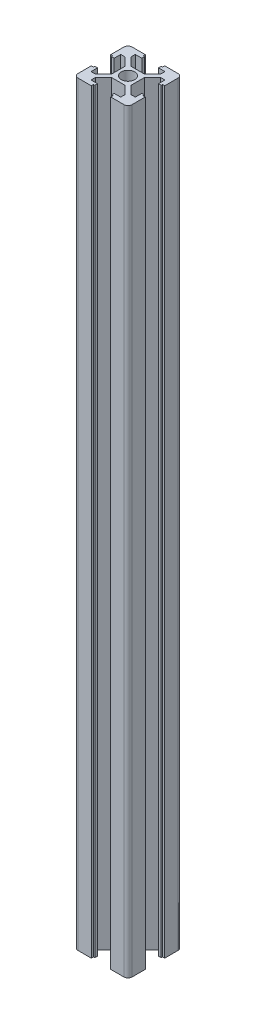
SolidWorks part; units mm, degrees
ref_plane "前视基准面" through (0, 0, 0) normal (0, 0, 1) x (1, 0, 0)
ref_plane "上视基准面" through (0, 0, 0) normal (0, 1, 0) x (1, 0, 0)
ref_plane "右视基准面" through (0, 0, 0) normal (1, 0, 0) x (0, 0, -1)
other "Configuration Table"
sketch "草图1" plane through (0, 0, 0) normal (0, 1, 0) x (1, 0, 0)
  line L0 (15.7522, 51.0126) -> (15.7522, 54.1126) construction
  line L1 (15.7522, 53.552) -> (15.7522, 48.4733)
  line L2 (21.8915, 54.6126) -> (16.8128, 54.6126)
  line L3 (22.9522, 48.4733) -> (22.9522, 53.552)
  line L4 (16.8128, 47.4126) -> (21.8915, 47.4126)
  line L5 (9.3522, 51.0126) -> (29.3522, 51.0126) construction
  line L6 (19.3522, 61.0126) -> (19.3522, 41.0126) construction
  line L7 (9.3522, 61.0126) -> (19.3522, 51.0126) construction
  line L8 (9.3522, 54.6126) -> (15.7522, 54.6126) construction
  line L9 (10.1522, 54.1126) -> (16.2522, 54.1126) construction
  line L10 (11.1522, 56.5126) -> (13.8522, 56.5126) construction
  line L11 (12.7915, 56.5126) -> (15.7522, 53.552) construction
  line L12 (9.3522, 59.5126) -> (9.3522, 54.6126)
  line L13 (9.3522, 54.6126) -> (10.1522, 54.6126)
  line L14 (10.1522, 54.6126) -> (10.1522, 54.1126)
  line L15 (10.1522, 54.1126) -> (11.1522, 54.1126)
  line L16 (11.1522, 54.1126) -> (11.1522, 56.5126)
  line L17 (11.1522, 56.5126) -> (12.7915, 56.5126)
  line L18 (12.7915, 56.5126) -> (15.7522, 53.552)
  line L19 (16.2522, 60.2126) -> (16.2522, 59.2126)
  line L20 (15.7522, 60.2126) -> (16.2522, 60.2126)
  line L21 (15.7522, 61.0126) -> (15.7522, 60.2126)
  line L22 (10.8522, 61.0126) -> (15.7522, 61.0126)
  line L23 (16.2522, 59.2126) -> (13.8522, 59.2126)
  line L24 (13.8522, 59.2126) -> (13.8522, 57.5733)
  line L25 (13.8522, 57.5733) -> (16.8128, 54.6126)
  line L26 (29.3522, 61.0126) -> (19.3522, 51.0126) construction
  line L27 (24.8522, 57.5733) -> (21.8915, 54.6126)
  line L28 (24.8522, 59.2126) -> (24.8522, 57.5733)
  line L29 (22.4522, 59.2126) -> (24.8522, 59.2126)
  line L30 (22.4522, 60.2126) -> (22.4522, 59.2126)
  line L31 (22.9522, 60.2126) -> (22.4522, 60.2126)
  line L32 (22.9522, 61.0126) -> (22.9522, 60.2126)
  line L33 (27.8522, 61.0126) -> (22.9522, 61.0126)
  line L34 (29.3522, 59.5126) -> (29.3522, 54.6126)
  line L35 (29.3522, 54.6126) -> (28.5522, 54.6126)
  line L36 (28.5522, 54.6126) -> (28.5522, 54.1126)
  line L37 (28.5522, 54.1126) -> (27.5522, 54.1126)
  line L38 (27.5522, 54.1126) -> (27.5522, 56.5126)
  line L39 (27.5522, 56.5126) -> (25.9128, 56.5126)
  line L40 (25.9128, 56.5126) -> (22.9522, 53.552)
  line L41 (29.3522, 41.0126) -> (19.3522, 51.0126) construction
  line L42 (25.9128, 45.5126) -> (22.9522, 48.4733)
  line L43 (27.5522, 45.5126) -> (25.9128, 45.5126)
  line L44 (27.5522, 47.9126) -> (27.5522, 45.5126)
  line L45 (28.5522, 47.9126) -> (27.5522, 47.9126)
  line L46 (28.5522, 47.4126) -> (28.5522, 47.9126)
  line L47 (29.3522, 47.4126) -> (28.5522, 47.4126)
  line L48 (29.3522, 42.5126) -> (29.3522, 47.4126)
  line L49 (27.8522, 41.0126) -> (22.9522, 41.0126)
  line L50 (22.9522, 41.0126) -> (22.9522, 41.8126)
  line L51 (22.9522, 41.8126) -> (22.4522, 41.8126)
  line L52 (22.4522, 41.8126) -> (22.4522, 42.8126)
  line L53 (22.4522, 42.8126) -> (24.8522, 42.8126)
  line L54 (24.8522, 42.8126) -> (24.8522, 44.452)
  line L55 (24.8522, 44.452) -> (21.8915, 47.4126)
  line L56 (9.3522, 41.0126) -> (19.3522, 51.0126) construction
  line L57 (13.8522, 44.452) -> (16.8128, 47.4126)
  line L58 (13.8522, 42.8126) -> (13.8522, 44.452)
  line L59 (16.2522, 42.8126) -> (13.8522, 42.8126)
  line L60 (16.2522, 41.8126) -> (16.2522, 42.8126)
  line L61 (15.7522, 41.8126) -> (16.2522, 41.8126)
  line L62 (15.7522, 41.0126) -> (15.7522, 41.8126)
  line L63 (10.8522, 41.0126) -> (15.7522, 41.0126)
  line L64 (9.3522, 42.5126) -> (9.3522, 47.4126)
  line L65 (9.3522, 47.4126) -> (10.1522, 47.4126)
  line L66 (10.1522, 47.4126) -> (10.1522, 47.9126)
  line L67 (10.1522, 47.9126) -> (11.1522, 47.9126)
  line L68 (11.1522, 47.9126) -> (11.1522, 45.5126)
  line L69 (11.1522, 45.5126) -> (12.7915, 45.5126)
  line L70 (12.7915, 45.5126) -> (15.7522, 48.4733)
  arc A0 (9.3522, 59.5126) -> (10.8522, 61.0126) centre (10.8522, 59.5126) cw
  circle A1 centre (19.3522, 51.0126) radius 2.5
  arc A2 (27.8522, 61.0126) -> (29.3522, 59.5126) centre (27.8522, 59.5126) cw
  arc A3 (29.3522, 42.5126) -> (27.8522, 41.0126) centre (27.8522, 42.5126) cw
  arc A4 (10.8522, 41.0126) -> (9.3522, 42.5126) centre (10.8522, 42.5126) cw
  point P13 (19.3522, 51.0126)
  point P84 (19.3522, 51.0126)
  dimension "D8" = 1.5
  dimension "D9" = 5
  dimension "D1" = 20
  dimension "D2" = 6.2
  dimension "D3" = 7.2
  dimension "D4" = 11
  dimension "D5" = 1.5
  dimension "D6" = 0.8
  dimension "D7" = 1.8
  dimension "D10" = 7.2
extrude "凸台-拉伸1" add sketch "草图1" along normal mid plane 280
